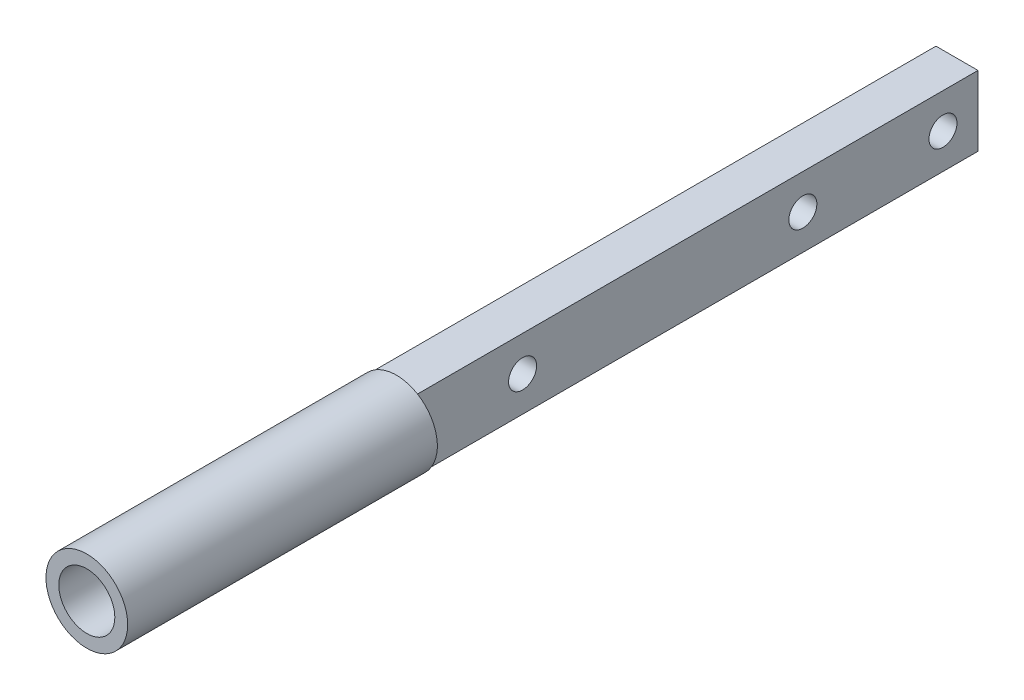
SolidWorks part; units mm, degrees
ref_plane "Plan de face" through (0, 0, 0) normal (0, 0, 1) x (1, 0, 0)
ref_plane "Plan de dessus" through (0, 0, 0) normal (0, 1, 0) x (1, 0, 0)
ref_plane "Plan de droite" through (0, 0, 0) normal (1, 0, 0) x (0, 0, -1)
sketch "Esquisse1" plane through (0, 0, 0) normal (0, 0, 1) x (1, 0, 0)
  line L0 (-15, 25) -> (15, -25) construction
  line L1 (-15, 25) -> (15, 25)
  line L2 (-15, 25) -> (-15, -25)
  line L3 (-15, -25) -> (15, -25)
  line L4 (15, 25) -> (15, -25)
  point P4 (0, 0)
  dimension "D1" = 30
  dimension "D2" = 50
extrude "Boss.-Extru.1" add sketch "Esquisse1" along normal blind 400
sketch "Esquisse2" plane through (0, 0, 400) normal (0, 0, 1) x (1, 0, 0)
  circle A0 centre (0, 0) radius 29.1548
extrude "Boss.-Extru.2" add sketch "Esquisse2" along normal blind 221
sketch "Esquisse3" plane through (0, 0, 621) normal (0, 0, 1) x (1, 0, 0)
  circle A0 centre (0, 0) radius 20
  dimension "D1" = 40
extrude "Enlèv. mat.-Extru.1" cut sketch "Esquisse3" against normal blind 195
sketch "Esquisse4" plane through (15, 0, 0) normal (1, 0, 0) x (0, 0, -1)
  line L0 (0, 25) -> (-25, 25) construction
  line L1 (-400, 25) -> (0, 25) construction
  line L2 (-25, 25) -> (-25, -25) construction
  line L3 (-400, -25) -> (0, -25) construction
  line L4 (0, 0) -> (-229.8977, 0) construction
  line L5 (0, -25) -> (0, 25) construction
  circle A0 centre (-25, 0) radius 10
  circle A1 centre (-125, 0) radius 10
  circle A2 centre (-325, 0) radius 10
  dimension "D2" = 20
  dimension "D3" = 20
  dimension "D5" = 20
  dimension "D1" = 25
  dimension "D4" = 100
  dimension "D6" = 200
extrude "Enlèv. mat.-Extru.2" cut sketch "Esquisse4" against normal up to next
